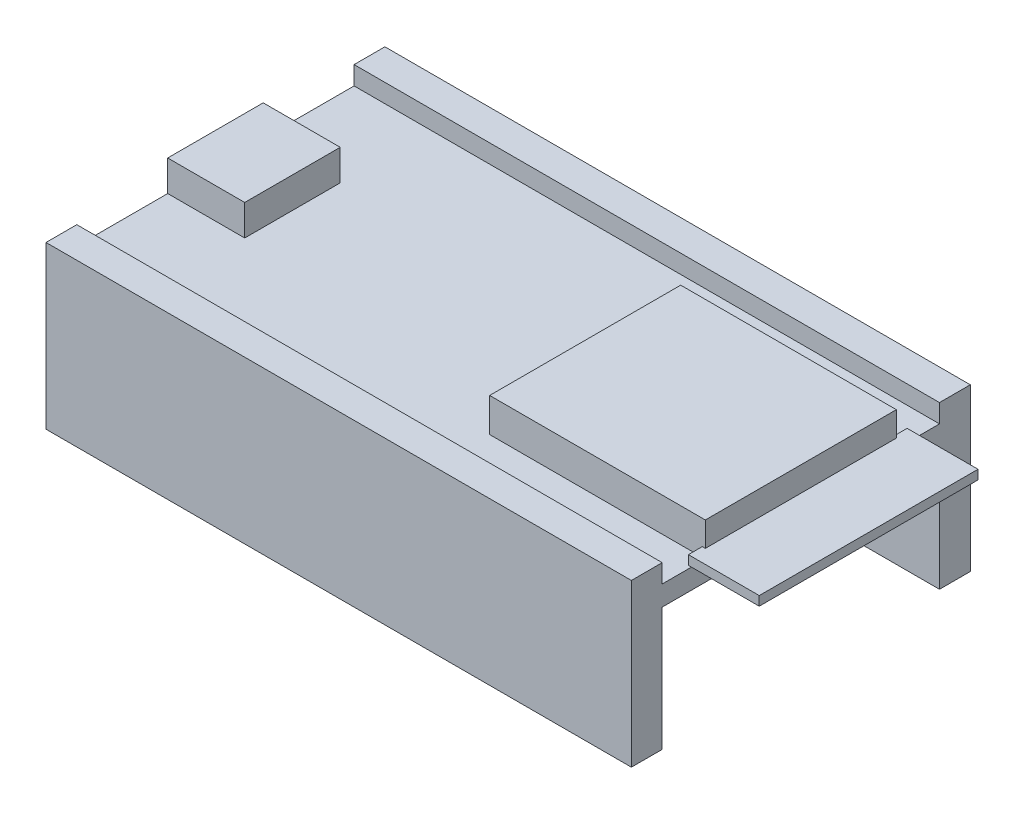
SolidWorks part; units mm, degrees
ref_plane "Front Plane" through (0, 0, 0) normal (0, 0, 1) x (1, 0, 0)
ref_plane "Top Plane" through (0, 0, 0) normal (0, 1, 0) x (1, 0, 0)
ref_plane "Right Plane" through (0, 0, 0) normal (1, 0, 0) x (0, 0, -1)
sketch "Sketch1" plane through (0, 0, 0) normal (0, 1, 0) x (1, 0, 0)
  line L1 (-24.13, 13.97) -> (24.13, 13.97)
  line L2 (-24.13, 13.97) -> (-24.13, -13.97)
  line L3 (-24.13, -13.97) -> (24.13, -13.97)
  line L4 (24.13, 13.97) -> (24.13, -13.97)
  line L5 (-24.13, 13.97) -> (24.13, -13.97) construction
  line L6 (-24.13, -13.97) -> (24.13, 13.97) construction
  point P0 (0, 0)
  dimension "D1" = 27.94
  dimension "D2" = 48.26
extrude "Boss-Extrude1" add sketch "Sketch1" along normal blind 1.651
sketch "Sketch2" plane through (0, 1.651, 0) normal (0, 1, 0) x (1, 0, 0)
  line L0 (24.13, -13.97) -> (24.13, 13.97) construction
  line L1 (-24.13, -13.97) -> (24.13, -13.97)
  line L2 (-24.13, -13.97) -> (-24.13, -11.43)
  line L3 (-24.13, -11.43) -> (24.13, -11.43)
  line L4 (24.13, -13.97) -> (24.13, -11.43)
  dimension "D1" = 2.54
extrude "Boss-Extrude2" add sketch "Sketch2" along normal blind 1.524 and the other way offset from surface (11.811 mm away) 10.16 other way up to face at (0, 0, 0)
mirror "Mirror1" about plane through (0, 0, 0) normal (0, 0, 1) of "Boss-Extrude2"
sketch "Sketch3" plane through (0, 1.651, 0) normal (0, 1, 0) x (1, 0, 0)
  line L0 (24.13, -11.43) -> (24.13, 11.43) construction
  line L1 (6.35, 7.874) -> (24.13, 7.874)
  line L2 (6.35, 7.874) -> (6.35, -7.874)
  line L3 (6.35, -7.874) -> (24.13, -7.874)
  line L4 (24.13, 7.874) -> (24.13, -7.874)
  line L5 (6.35, 7.874) -> (24.13, -7.874) construction
  line L6 (6.35, -7.874) -> (24.13, 7.874) construction
  line L9 (0, 0) -> (24.13, 0) construction
  point P0 (15.24, 0)
  dimension "D1" = 17.78
  dimension "D2" = 15.748
extrude "Boss-Extrude3" add sketch "Sketch3" along normal blind 2.794
sketch "Sketch4" plane through (24.13, 0, 0) normal (1, 0, 0) x (0, 0, -1)
  line L0 (-11.43, 1.651) -> (-7.874, 1.651) construction
  line L1 (-9.017, 1.651) -> (9.017, 1.651)
  line L2 (-9.017, 1.651) -> (-9.017, 2.413)
  line L3 (-9.017, 2.413) -> (9.017, 2.413)
  line L4 (9.017, 1.651) -> (9.017, 2.413)
  line L6 (0, 0) -> (0, 6.5362) construction
  dimension "D1" = 0.762
  dimension "D2" = 18.034
extrude "Boss-Extrude6" add sketch "Sketch4" along normal blind 5.588 and the other way blind 0.254
sketch "Sketch5" plane through (0, 1.651, 0) normal (0, 1, 0) x (1, 0, 0)
  line L0 (-24.13, 11.43) -> (-24.13, -11.43) construction
  line L1 (-24.13, 3.937) -> (-17.78, 3.937)
  line L2 (-24.13, 3.937) -> (-24.13, -3.937)
  line L3 (-24.13, -3.937) -> (-17.78, -3.937)
  line L4 (-17.78, 3.937) -> (-17.78, -3.937)
  line L5 (0, 0) -> (-24.13, 0) construction
  dimension "D1" = 7.874
  dimension "D2" = 6.35
extrude "Boss-Extrude7" add sketch "Sketch5" along normal blind 2.54
